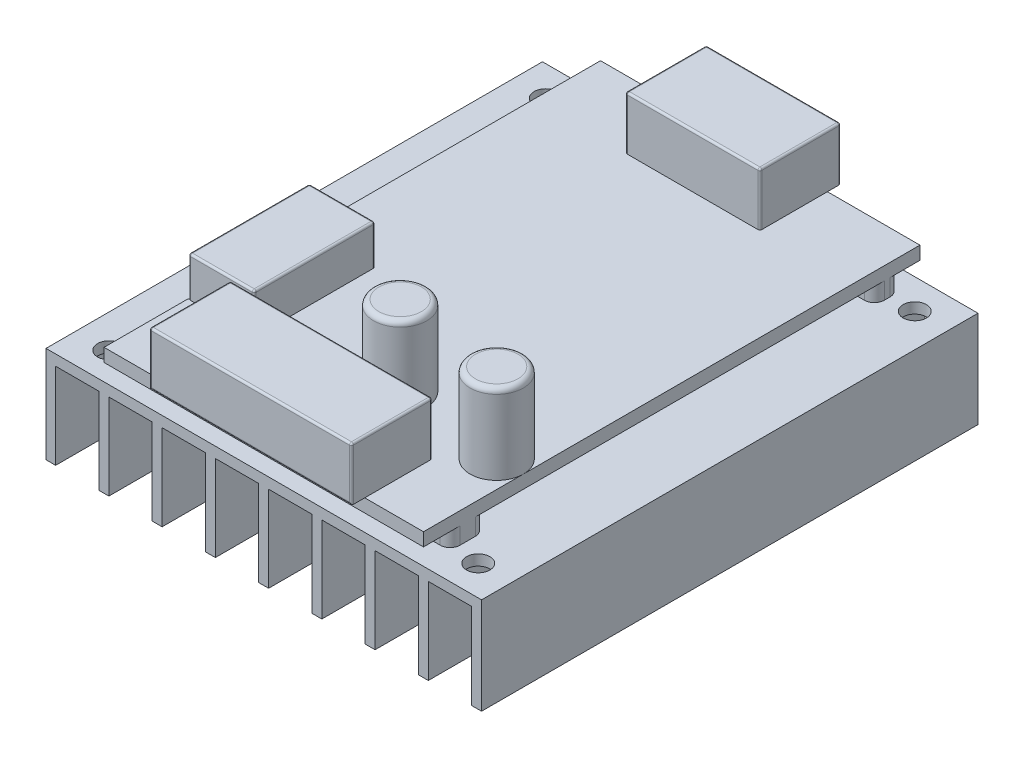
SolidWorks part; units mm, degrees
ref_plane "Frontal" through (0, 0, 0) normal (0, 0, 1) x (1, 0, 0)
ref_plane "Superior" through (0, 0, 0) normal (0, 1, 0) x (1, 0, 0)
ref_plane "Direito" through (0, 0, 0) normal (1, 0, 0) x (0, 0, -1)
sketch "Esboço2" plane through (0, 0, 0) normal (0, 1, 0) x (1, 0, 0)
  line L0 (0, 0) -> (0, 8.5834) construction
  line L1 (32.725, -37.3) -> (-32.725, -37.3)
  line L2 (32.725, -37.3) -> (32.725, 37.3)
  line L3 (32.725, 37.3) -> (-32.725, 37.3)
  line L4 (-32.725, -37.3) -> (-32.725, 37.3)
  line L5 (32.725, -37.3) -> (-32.725, 37.3) construction
  line L6 (32.725, 37.3) -> (-32.725, -37.3) construction
  line L7 (0, 0) -> (8.4296, 0) construction
  circle A0 centre (27.725, 32.8) radius 1.75
  circle A1 centre (-27.725, 32.8) radius 1.75
  circle A2 centre (27.725, -32.8) radius 1.75
  circle A3 centre (-27.725, -32.8) radius 1.75
  point P0 (0, 0)
  point P11 (0, 0)
  point P13 (0, 0)
  dimension "D4" = 3.5
  dimension "D1" = 65.45
  dimension "D2" = 74.6
  dimension "D3" = 5
  dimension "D5" = 4.5
extrude "Ressalto-extrusão1" add sketch "Esboço2" against normal blind 14.5
sketch "Esboço3" plane through (0, 0, -37.3) normal (0, 0, -1) x (-1, 0, 0)
  line L0 (-31.225, -14.5) -> (-31.225, -1.6)
  line L1 (-31.225, -14.5) -> (-24.725, -14.5)
  line L2 (-31.225, -1.6) -> (-24.725, -1.6)
  line L3 (-24.725, -14.5) -> (-24.725, -1.6)
  line L4 (-32.725, -14.5) -> (32.725, -14.5) construction
  line L5 (-32.725, -14.5) -> (-32.725, 0) construction
  line L6 (-32.725, 0) -> (32.725, 0) construction
  line L7 (-23.225, -14.5) -> (-23.225, -1.6)
  line L8 (-23.225, -14.5) -> (-16.725, -14.5)
  line L9 (-23.225, -1.6) -> (-16.725, -1.6)
  line L10 (-16.725, -14.5) -> (-16.725, -1.6)
  line L11 (-15.225, -14.5) -> (-15.225, -1.6)
  line L12 (-15.225, -14.5) -> (-8.725, -14.5)
  line L13 (-15.225, -1.6) -> (-8.725, -1.6)
  line L14 (-8.725, -14.5) -> (-8.725, -1.6)
  line L15 (-7.225, -14.5) -> (-7.225, -1.6)
  line L16 (-7.225, -14.5) -> (-0.725, -14.5)
  line L17 (-7.225, -1.6) -> (-0.725, -1.6)
  line L18 (-0.725, -14.5) -> (-0.725, -1.6)
  line L19 (0.775, -14.5) -> (0.775, -1.6)
  line L20 (0.775, -14.5) -> (7.275, -14.5)
  line L21 (0.775, -1.6) -> (7.275, -1.6)
  line L22 (7.275, -14.5) -> (7.275, -1.6)
  line L23 (8.775, -14.5) -> (8.775, -1.6)
  line L24 (8.775, -14.5) -> (15.275, -14.5)
  line L25 (8.775, -1.6) -> (15.275, -1.6)
  line L26 (15.275, -14.5) -> (15.275, -1.6)
  line L27 (16.775, -14.5) -> (16.775, -1.6)
  line L28 (16.775, -14.5) -> (23.275, -14.5)
  line L29 (16.775, -1.6) -> (23.275, -1.6)
  line L30 (23.275, -14.5) -> (23.275, -1.6)
  line L31 (24.775, -14.5) -> (24.775, -1.6)
  line L32 (24.775, -14.5) -> (31.275, -14.5)
  line L33 (24.775, -1.6) -> (31.275, -1.6)
  line L34 (31.275, -14.5) -> (31.275, -1.6)
  dimension "D1" = 1.5
  dimension "D2" = 1.6
  dimension "D3" = 6.5
  dimension "D4" = 8
extrude "Corte-extrusão1" cut sketch "Esboço3" against normal up to next
sketch "Esboço4" plane through (0, 0, 0) normal (0, 1, 0) x (1, 0, 0)
  line L0 (-24, 37.3) -> (24, 37.3)
  line L1 (-24, 37.3) -> (-24, -37.3)
  line L2 (24, 37.3) -> (24, -37.3)
  line L3 (-24, -37.3) -> (24, -37.3)
  line L5 (-32.725, -37.3) -> (32.725, -37.3) construction
  line L6 (0, 0) -> (0, 37.3) construction
  line L7 (32.725, 37.3) -> (-32.725, 37.3) construction
  point P6 (0, 0)
  point P12 (0, 0)
  point P13 (0, 0)
  point P14 (0, 0)
  dimension "D1" = 48
  dimension "D2" = 0
extrude "Ressalto-extrusão2" add sketch "Esboço4" along normal blind 4.5
sketch "Esboço5" plane through (0, 4.5, 0) normal (0, 1, 0) x (1, 0, 0)
  line L0 (-10.1, 39.3) -> (10.1, 39.3)
  line L1 (-10.1, 39.3) -> (-10.1, 27.15)
  line L2 (10.1, 39.3) -> (10.1, 27.15)
  line L3 (-10.1, 27.15) -> (10.1, 27.15)
  line L4 (0, 39.3) -> (0, 0) construction
  line L5 (24, 37.3) -> (-24, 37.3) construction
  line L6 (15.175, -39.3) -> (-15.175, -39.3)
  line L7 (15.175, -39.3) -> (15.175, -27.15)
  line L8 (-15.175, -39.3) -> (-15.175, -27.15)
  line L9 (15.175, -27.15) -> (-15.175, -27.15)
  line L10 (0, -39.3) -> (0, 0) construction
  line L11 (-24, -37.3) -> (24, -37.3) construction
  dimension "D1" = 2
  dimension "D2" = 20.2
  dimension "D3" = 12.15
  dimension "D4" = 30.35
  dimension "D5" = 2
  dimension "D6" = 12.15
extrude "Ressalto-extrusão3" add sketch "Esboço5" along normal blind 8
sketch "Esboço6" plane through (0, 4.5, 0) normal (0, 1, 0) x (1, 0, 0)
  line L3 (-15.175, -39.3) -> (15.175, -39.3) construction
  line L4 (24, -37.3) -> (24, 37.3) construction
  line L5 (15.175, -37.3) -> (24, -37.3) construction
  circle A0 centre (20, -22.3) radius 4
  circle A1 centre (4, -20.8) radius 4
  dimension "D1" = 8
  dimension "D4" = 8
  dimension "D2" = 4
  dimension "D3" = 15
  dimension "D5" = 20
  dimension "D6" = 18.5
extrude "Ressalto-extrusão4" add sketch "Esboço6" along normal blind 12
fillet "Filete1" radius 0.8 2 edges at (4, 16.5, 24.8) (20, 16.5, 26.3)
sketch "Esboço7" plane through (0, 0, -37.3) normal (0, 0, -1) x (-1, 0, 0)
  line L0 (-20.0904, 2.522) -> (20.2778, 2.522)
  line L1 (-20.0904, 2.522) -> (-20.0904, 0)
  line L2 (20.2778, 2.522) -> (20.2778, 0)
  line L3 (-20.0904, 0) -> (20.2778, 0)
  line L4 (-24, 0) -> (-32.725, 0) construction
  point P0 (0, 0)
extrude "Corte-extrusão2" cut sketch "Esboço7" against normal up to next
sketch "Esboço8" plane through (-24, 0, 0) normal (-1, 0, 0) x (0, 0, 1)
  line L0 (-30.453, 2.522) -> (28.0153, 2.522)
  line L1 (-30.453, 2.522) -> (-30.453, 0)
  line L2 (28.0153, 2.522) -> (28.0153, 0)
  line L3 (-30.453, 0) -> (28.0153, 0)
  line L4 (-37.3, 0) -> (37.3, 0) construction
  point P0 (28.0153, 2.6645)
extrude "Corte-extrusão3" cut sketch "Esboço8" against normal through all
sketch "Esboço9" plane through (0, 0, 37.3) normal (0, 0, 1) x (1, 0, 0)
  line L0 (-20.2778, 2.522) -> (-24, 2.522)
  line L1 (-20.2778, 2.522) -> (-20.2778, 0)
  line L2 (-24, 2.522) -> (-24, 0)
  line L3 (-20.2778, 0) -> (-24, 0)
  line L4 (-24, 4.5) -> (-24, 0) construction
  line L5 (20.0904, 2.522) -> (24, 2.522)
  line L6 (20.0904, 2.522) -> (20.0904, 0)
  line L7 (24, 2.522) -> (24, 0)
  line L8 (20.0904, 0) -> (24, 0)
  line L9 (24, 4.5) -> (24, 0) construction
  line L10 (24, 0) -> (32.725, 0) construction
  line L11 (20.0904, 0) -> (-20.2778, 0) construction
  point P16 (0, 0)
  point P19 (0, 0)
extrude "Corte-extrusão4" cut sketch "Esboço9" against normal blind 4
sketch "Esboço10" plane through (0, 0, -37.3) normal (0, 0, -1) x (-1, 0, 0)
  line L0 (-20.0904, 2.522) -> (-24, 2.522)
  line L1 (-20.0904, 2.522) -> (-20.0904, 0)
  line L2 (-24, 2.522) -> (-24, 0)
  line L3 (-20.0904, 0) -> (-24, 0)
  line L4 (-24, 4.5) -> (-24, 0) construction
  line L5 (20.2778, 2.522) -> (24, 2.522)
  line L6 (20.2778, 2.522) -> (20.2778, 0)
  line L7 (24, 2.522) -> (24, 0)
  line L8 (20.2778, 0) -> (24, 0)
  line L9 (24, 4.5) -> (24, 0) construction
  line L10 (-20.0904, 0) -> (20.2778, 0) construction
  line L11 (-20.0904, 0) -> (20.2778, 0) construction
  point P16 (0, 0)
  point P19 (0, 0)
  point P20 (0, 0)
  point P21 (0, 0)
  point P22 (0, 0)
extrude "Corte-extrusão5" cut sketch "Esboço10" against normal blind 3
fillet "Filete2" radius 1.5 16 edges at (-20.2778, 1.261, 28.0153) (-20.2778, 1.261, 33.3) (-24, 1.261, 28.0153) (-24, 1.261, 33.3) (20.0904, 1.261, 33.3) (20.0904, 1.261, 28.0153) (24, 1.261, 28.0153) (24, 1.261, 33.3) (20.0904, 1.261, -30.453) (24, 1.261, -30.453) (20.0904, 1.261, -34.3) (24, 1.261, -34.3) (-20.2778, 1.261, -30.453) (-20.2778, 1.261, -34.3) (-24, 1.261, -30.453) (-24, 1.261, -34.3)
fillet "Filete3" radius 0.3 18 edges at (0, 4.5, 39.3) (-10.1, 8.5, -39.3) (0, 12.5, -39.3) (0, 4.5, -39.3) (10.1, 8.5, -39.3) (10.1, 12.5, -33.225) (10.1, 8.5, -27.15) (-10.1, 8.5, -27.15) (-10.1, 12.5, -33.225) (0, 12.5, -27.15) (-15.175, 8.5, 27.15) (-15.175, 8.5, 39.3) (-15.175, 12.5, 33.225) (0, 12.5, 27.15) (15.175, 8.5, 27.15) (15.175, 12.5, 33.225) (15.175, 8.5, 39.3) (0, 12.5, 39.3)
sketch "Esboço11" plane through (0, 4.5, 0) normal (0, 1, 0) x (1, 0, 0)
  line L0 (-24, -24.697) -> (-24, -6.5512)
  line L1 (-24, -24.697) -> (-14.0391, -24.697)
  line L2 (-24, -6.5512) -> (-14.0391, -6.5512)
  line L3 (-14.0391, -24.697) -> (-14.0391, -6.5512)
  line L4 (-24, 37.3) -> (-24, -37.3) construction
extrude "Ressalto-extrusão5" add sketch "Esboço11" along normal blind 6
sketch "Esboço12" plane through (-24, 0, 0) normal (-1, 0, 0) x (0, 0, 1)
  line L0 (6.5512, 10.5) -> (24.697, 10.5)
  line L1 (6.5512, 10.5) -> (6.5512, 4.3451)
  line L2 (24.697, 10.5) -> (24.697, 4.3451)
  line L3 (6.5512, 4.3451) -> (24.697, 4.3451)
extrude "Corte-extrusão6" cut sketch "Esboço12" against normal blind 0.1
fillet "Filete4" radius 0.3 8 edges at (-14.0391, 7.5, 6.5512) (-23.9, 7.5, 6.5512) (-18.9695, 10.5, 6.5512) (-14.0391, 10.5, 15.6241) (-14.0391, 7.5, 24.697) (-23.9, 10.5, 15.6241) (-18.9695, 10.5, 24.697) (-23.9, 7.5, 24.697)
